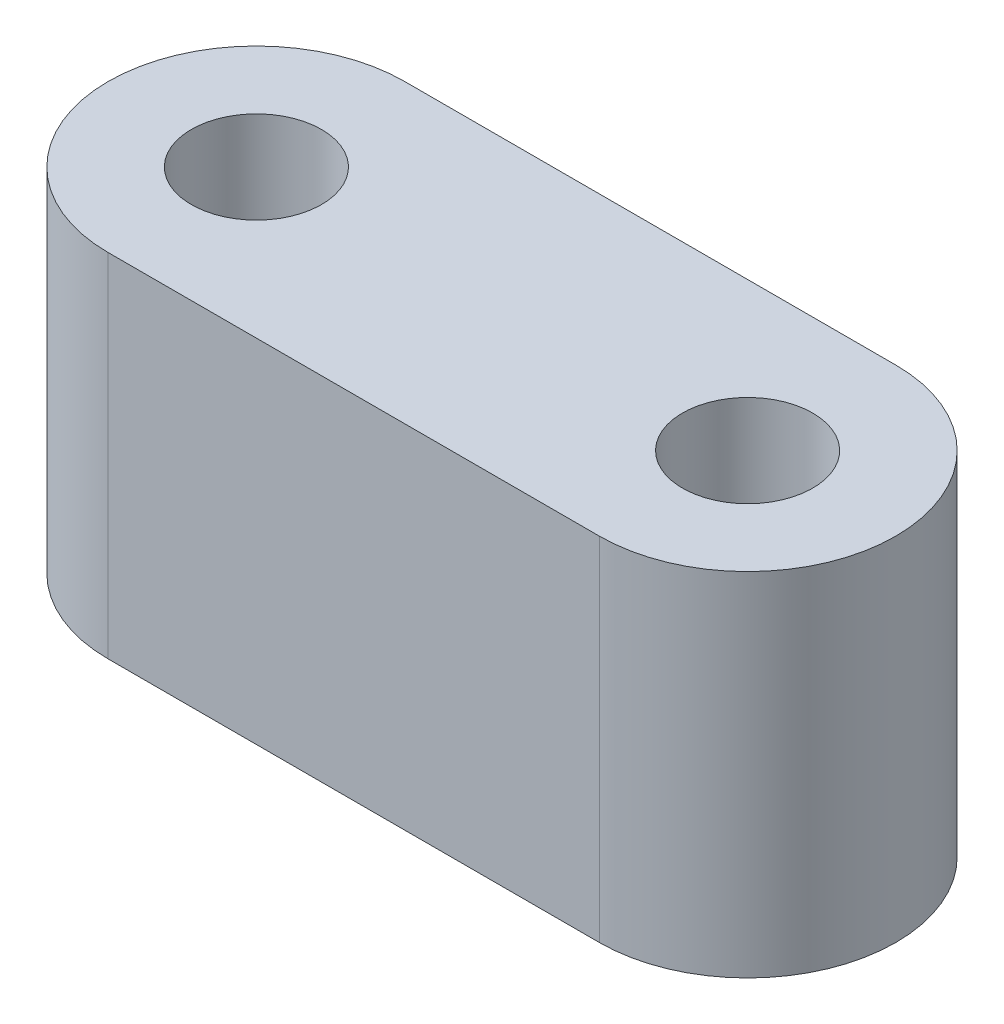
SolidWorks part; units mm, degrees
ref_plane "Front Plane" through (0, 0, 0) normal (0, 0, 1) x (1, 0, 0)
ref_plane "Top Plane" through (0, 0, 0) normal (0, 1, 0) x (1, 0, 0)
ref_plane "Right Plane" through (0, 0, 0) normal (1, 0, 0) x (0, 0, -1)
sketch "Sketch1" plane through (0, 0, 0) normal (0, 1, 0) x (1, 0, 0)
  line L0 (-26.9408, 0) -> (0, 0) construction
  line L1 (-26.9408, 8.128) -> (0, 8.128)
  line L2 (-26.9408, -8.128) -> (0, -8.128)
  arc A0 (-26.9408, 8.128) -> (-26.9408, -8.128) centre (-26.9408, 0) ccw
  arc A1 (0, -8.128) -> (0, 8.128) centre (0, 0) ccw
  point P3 (-13.4704, 0)
  dimension "D1" = 8.128
  dimension "D2" = 26.9408
extrude "Boss-Extrude1" add sketch "Sketch1" along normal blind 19.304
sketch "Sketch4" plane through (0, 0, 0) normal (0, -1, 0) x (-1, 0, 0)
  point P0 (0, 0)
  point P3 (26.9408, 0)
hole_wizard "1/4 Clearance Hole1" positions "Sketch4" profile "Sketch3" hole size "1/4" standard "ANSI Inch" end condition through all
sketch "Sketch3" plane through (0, 0, 0) normal (1, 0, 0) x (0, 0, -1)
  line L0 (0, 0) -> (0, 19.304)
  line L1 (0, 19.304) -> (3.5712, 19.304)
  line L2 (3.5712, 19.304) -> (3.5712, 0)
  line L5 (3.5712, 0) -> (0, 0)
  line L11 (0, -6.35) -> (0, 107.95) construction
  dimension "Thru Hole Dia." = 7.1425
  dimension "Thru Hole Depth" = 19.304
